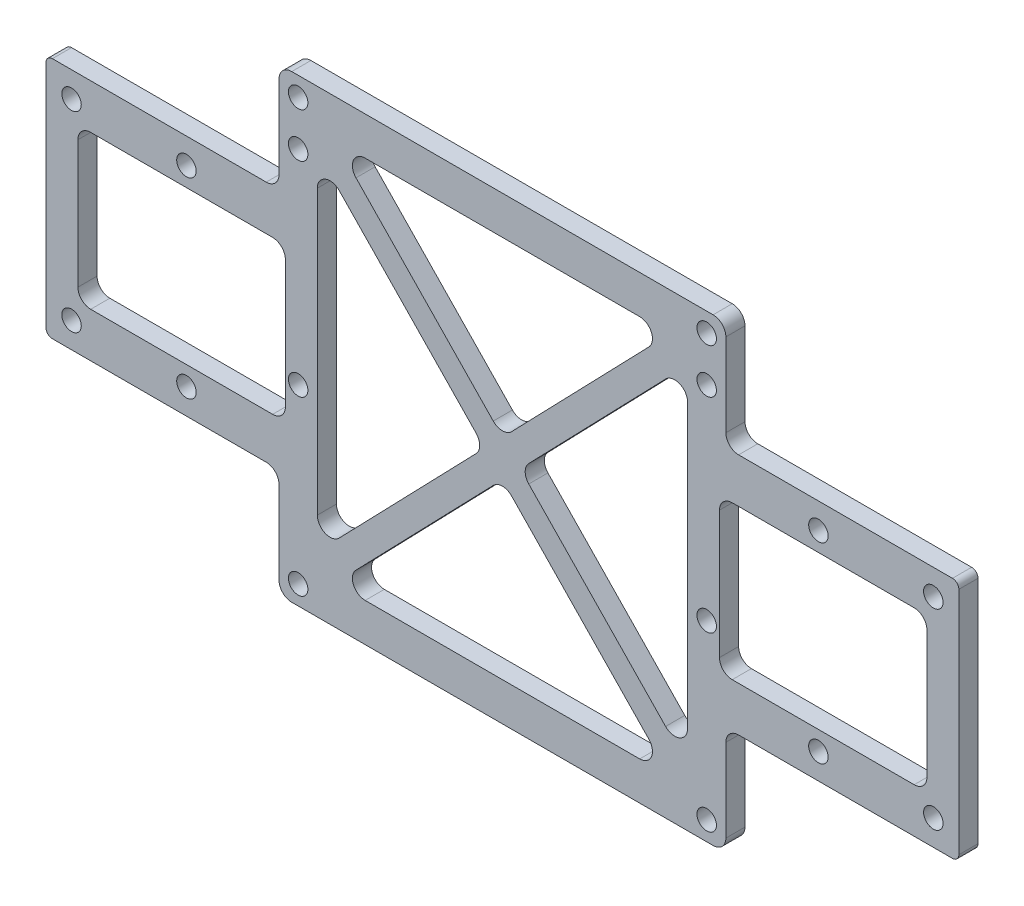
SolidWorks part; units mm, degrees
material "Thornel Mat VMA"
ref_plane "前视基准面" through (0, 0, 0) normal (0, 0, 1) x (1, 0, 0)
ref_plane "上视基准面" through (0, 0, 0) normal (0, 1, 0) x (1, 0, 0)
ref_plane "右视基准面" through (0, 0, 0) normal (1, 0, 0) x (0, 0, -1)
other "Configuration Table"
sketch "草图1" plane through (0, 0, 0) normal (0, 0, 1) x (1, 0, 0)
  line L1 (-67.5, -15) -> (67.5, -15) construction
  line L2 (-67.5, -15) -> (-67.5, 15) construction
  line L3 (-67.5, 15) -> (67.5, 15) construction
  line L4 (67.5, -15) -> (67.5, 15) construction
  line L5 (-67.5, -15) -> (67.5, 15) construction
  line L6 (-67.5, 15) -> (67.5, -15) construction
  line L7 (-71.5, -19) -> (71.5, -19)
  line L8 (-71.5, -19) -> (-71.5, 19)
  line L9 (-71.5, 19) -> (71.5, 19)
  line L10 (71.5, -19) -> (71.5, 19)
  line L11 (-71.5, -19) -> (71.5, 19) construction
  line L12 (-71.5, 19) -> (71.5, -19) construction
  circle A0 centre (67.5, 15) radius 1.525
  circle A1 centre (67.5, -15) radius 1.525
  circle A2 centre (-67.5, 15) radius 1.525
  circle A3 centre (-67.5, -15) radius 1.525
  point P0 (0, 0)
  point P10 (0, 0)
  dimension "D3" = 3.05
  dimension "D1" = 30
  dimension "D2" = 135
  dimension "D4" = 4
  dimension "D5" = 4
extrude "凸台-拉伸1" add sketch "草图1" along normal blind 3
sketch "草图2" plane through (0, 0, 3) normal (0, 0, 1) x (1, 0, 0)
  circle A0 centre (32, -6) radius 1.75 construction
  circle A1 centre (32, 26) radius 1.75 construction
  circle A2 centre (-32, -6) radius 1.75 construction
  circle A3 centre (-32, 26) radius 1.75 construction
  circle A4 centre (32, -6) radius 1.75 construction
  circle A5 centre (32, 26) radius 1.75 construction
  circle A6 centre (-32, -6) radius 1.75 construction
  circle A7 centre (-32, 26) radius 1.75 construction
  circle A8 centre (-32, 26) radius 1.525
  circle A9 centre (-32, -6) radius 1.525
  circle A10 centre (32, 26) radius 1.525
  circle A11 centre (32, -6) radius 1.525
  dimension "D1" = 3.05
extrude "切除-拉伸1" cut sketch "草图2" against normal blind 3
fillet "圆角1" radius 1 4 edges at (-71.5, 19, 1.5) (-71.5, -19, 1.5) (71.5, -19, 1.5) (71.5, 19, 1.5)
sketch "草图3" plane through (0, 0, 3) normal (0, 0, 1) x (1, 0, 0)
  line L0 (0, 10) -> (0, 0) construction
  line L5 (-35, -36) -> (35, -36)
  line L6 (-35, -36) -> (-35, 36)
  line L7 (-35, 36) -> (35, 36)
  line L8 (35, -36) -> (35, 36)
  line L9 (-35, -36) -> (35, 36) construction
  line L10 (-35, 36) -> (35, -36) construction
  line L11 (-32, 26) -> (32, 26) construction
  line L12 (-32, 26) -> (-32, -6) construction
  line L13 (-32, -6) -> (32, -6) construction
  line L14 (32, 26) -> (32, -6) construction
  line L15 (-32, 26) -> (32, -6) construction
  line L16 (-32, -6) -> (32, 26) construction
  circle A3 centre (-32, -6) radius 1.525 construction
  circle A4 centre (32, -6) radius 1.525 construction
  circle A5 centre (-32, 26) radius 1.525
  circle A6 centre (-32, -6) radius 1.525
  circle A7 centre (32, -6) radius 1.525
  circle A8 centre (32, 26) radius 1.525
  point P0 (0, 0)
  point P6 (0, 10)
  dimension "D1" = 72
  dimension "D2" = 32
  dimension "D3" = 3
extrude "凸台-拉伸2" add sketch "草图3" against normal up to surface (3 mm away) up to face at (-30.475, -6, 0)
fillet "圆角2" radius 2 8 edges at (35, 36, 1.5) (35, 19, 1.5) (35, -19, 1.5) (35, -36, 1.5) (-35, -36, 1.5) (-35, -19, 1.5) (-35, 19, 1.5) (-35, 36, 1.5)
sketch "草图4" plane through (0, 0, 3) normal (0, 0, 1) x (1, 0, 0)
  line L0 (33, 36) -> (-33, 36) construction
  line L1 (-32, -33) -> (32, -33) construction
  line L2 (-32, -33) -> (-32, 33) construction
  line L3 (-32, 33) -> (32, 33) construction
  line L4 (32, -33) -> (32, 33) construction
  line L5 (-32, -33) -> (32, 33) construction
  line L6 (-32, 33) -> (32, -33) construction
  line L7 (35, 21) -> (35, 34) construction
  circle A0 centre (32, 33) radius 1.525
  circle A1 centre (-32, 33) radius 1.525
  circle A2 centre (-32, -33) radius 1.525
  circle A3 centre (32, -33) radius 1.525
  point P0 (0, 0)
  dimension "D3" = 3.05
  dimension "D1" = 3
  dimension "D2" = 3
extrude "切除-拉伸2" cut sketch "草图4" against normal up to surface (3 mm away) up to face at (0, 0, 0)
sketch "草图5" plane through (0, 0, 3) normal (0, 0, 1) x (1, 0, 0)
  line L0 (30.438, -28.61) -> (-27.562, 31.39)
  line L1 (29, -30) -> (-29, -30)
  line L2 (29, -30) -> (29, 30)
  line L3 (29, 30) -> (-29, 30)
  line L4 (-29, -30) -> (-29, 30)
  line L5 (29, -30) -> (-29, 30) construction
  line L6 (29, 30) -> (-29, -30) construction
  line L7 (27.562, 31.39) -> (-30.438, -28.61)
  line L8 (27.562, -31.39) -> (-30.438, 28.61)
  line L9 (30.438, 28.61) -> (-27.562, -31.39)
  circle A1 centre (-32, 33) radius 1.525 construction
  circle A2 centre (32, -6) radius 1.525 construction
  point P0 (0, 0)
  dimension "D1" = 3
  dimension "D2" = 3
  dimension "D3" = 2
  dimension "D4" = 2
extrude "切除-拉伸3" cut sketch "草图5" against normal up to surface (3 mm away) contours L8 L9 L1 | L2 L9 L0 | L7 L8 L4 | L7 L3 L0 up to face at (30.475, -33, 0)
fillet "圆角3" radius 2 12 edges at (0, -2.8776, 1.5) (26.2183, -30, 1.5) (-26.2183, -30, 1.5) (26.2183, 30, 1.5) (0, 2.8776, 1.5) (-26.2183, 30, 1.5) (-2.7817, 0, 1.5) (-29, -27.1224, 1.5) (-29, 27.1224, 1.5) (2.7817, 0, 1.5) (29, -27.1224, 1.5) (29, 27.1224, 1.5)
sketch "草图6" plane through (0, 0, 0) normal (0, 0, -1) x (-1, 0, 0)
  line L0 (-58.5, 0) -> (0, 0) construction
  line L1 (-49.5, -15) -> (-67.5, -15) construction
  line L2 (-49.5, -15) -> (-49.5, 15) construction
  line L3 (-49.5, 15) -> (-67.5, 15) construction
  line L4 (-67.5, -15) -> (-67.5, 15) construction
  line L5 (-49.5, -15) -> (-67.5, 15) construction
  line L6 (-49.5, 15) -> (-67.5, -15) construction
  circle A0 centre (-49.5, 15) radius 1.525
  circle A1 centre (-49.5, -15) radius 1.525
  point P0 (-58.5, 0)
  dimension "D2" = 3.05
  dimension "D1" = 18
extrude "切除-拉伸4" cut sketch "草图6" against normal up to surface (3 mm away) up to face at (19.625, 0, 3)
mirror "镜向1" about plane through (0, 0, 0) normal (1, 0, 0) of "切除-拉伸4"
sketch "草图7" plane through (0, 0, 0) normal (0, 0, -1) x (-1, 0, 0)
  line L0 (-50.25, 0) -> (0, 0) construction
  line L1 (-66.5, -12) -> (-34, -12)
  line L2 (-66.5, -12) -> (-66.5, 12)
  line L3 (-66.5, 12) -> (-34, 12)
  line L4 (-34, -12) -> (-34, 12)
  line L5 (-66.5, -12) -> (-34, 12) construction
  line L6 (-66.5, 12) -> (-34, -12) construction
  line L7 (-71.5, -18) -> (-71.5, 18) construction
  line L8 (-29, -22.1758) -> (-29, 22.1758) construction
  circle A0 centre (-49.5, 15) radius 1.525 construction
  point P0 (-50.25, 0)
  dimension "D1" = 3
  dimension "D2" = 5
  dimension "D3" = 5
extrude "切除-拉伸5" cut sketch "草图7" against normal up to surface (3 mm away) up to face at (-51.025, 15, 3)
mirror "镜向2" about plane through (0, 0, 0) normal (1, 0, 0) of "切除-拉伸5"
fillet "圆角4" radius 2 8 edges at (-34, 12, 1.5) (-66.5, 12, 1.5) (-66.5, -12, 1.5) (-34, -12, 1.5) (66.5, 12, 1.5) (34, 12, 1.5) (66.5, -12, 1.5) (34, -12, 1.5)
